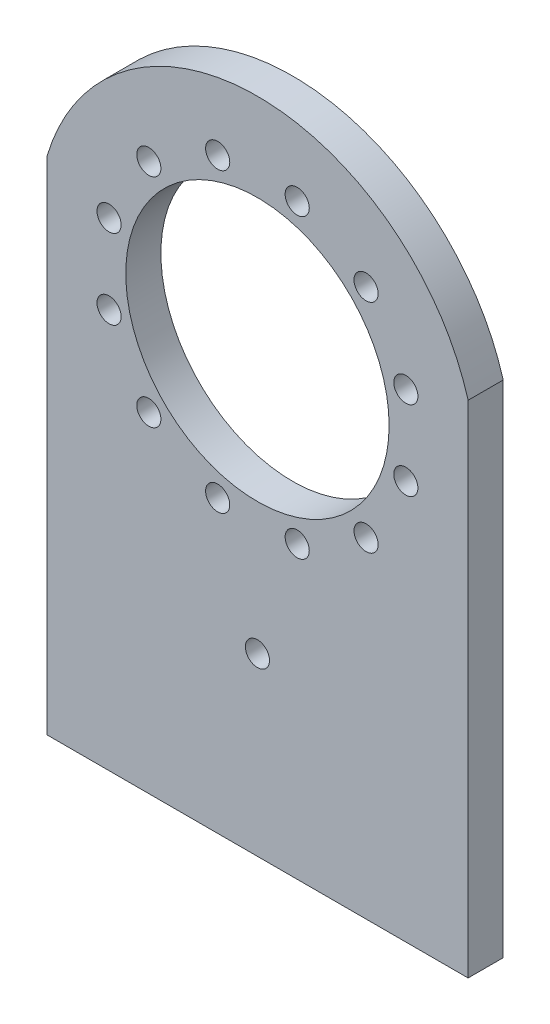
SolidWorks part; units mm, degrees
ref_plane "前视基准面" through (0, 0, 0) normal (0, 0, 1) x (1, 0, 0)
ref_plane "上视基准面" through (0, 0, 0) normal (0, 1, 0) x (1, 0, 0)
ref_plane "右视基准面" through (0, 0, 0) normal (1, 0, 0) x (0, 0, -1)
other "Configuration Table"
sketch "草图1" plane through (0, 0, 0) normal (0, 0, 1) x (1, 0, 0)
  line L0 (0, 0) -> (0, 150.9585) construction
  line L3 (-48, 114) -> (-48, 0)
  line L4 (-48, 0) -> (48, 0)
  line L5 (48, 114) -> (48, 0)
  circle A0 centre (0, 100) radius 30
  arc A2 (48, 114) -> (-48, 114) centre (0, 100) ccw
  dimension "D3" = 60
  dimension "D4" = 50
  dimension "D1" = 96
  dimension "D2" = 100
extrude "凸台-拉伸1" add sketch "草图1" along normal blind 8
sketch "草图2" plane through (0, 0, 0) normal (0, -1, 0) x (1, 0, 0)
  line L0 (-53.8408, 4) -> (58.1589, 4) construction
  line L1 (0, 20.308) -> (0, -17.9139) construction
  line L2 (-48, 8) -> (48, 8) construction
  line L3 (-48, 0) -> (48, 0) construction
  circle A0 centre (35, 4) radius 2.75
  circle A1 centre (-35, 4) radius 2.75
  dimension "D2" = 5.5
  dimension "D1" = 70
extrude "切除-拉伸1" cut sketch "草图2" against normal blind 50
sketch "草图3" plane through (0, 0, 8) normal (0, 0, 1) x (1, 0, 0)
  line L0 (0, 0) -> (0, 95.092) construction
  circle A0 centre (0, 40) radius 2.75
  dimension "D1" = 5.5
  dimension "D2" = 40
extrude "切除-拉伸2" cut sketch "草图3" against normal blind 20
sketch "草图4" plane through (0, 0, 8) normal (0, 0, 1) x (1, 0, 0)
  line L0 (0, 100) -> (0, 148.0466) construction
  line L1 (0, 100) -> (14.5496, 154.2997) construction
  circle A0 centre (9.0587, 133.8074) radius 2.75
  circle A1 centre (24.7487, 124.7487) radius 2.75
  circle A2 centre (33.8074, 109.0587) radius 2.75
  circle A3 centre (33.8074, 90.9413) radius 2.75
  circle A4 centre (24.7487, 75.2513) radius 2.75
  circle A5 centre (9.0587, 66.1926) radius 2.75
  circle A6 centre (-9.0587, 66.1926) radius 2.75
  circle A7 centre (-24.7487, 75.2513) radius 2.75
  circle A8 centre (-33.8074, 90.9413) radius 2.75
  circle A9 centre (-33.8074, 109.0587) radius 2.75
  circle A10 centre (-24.7487, 124.7487) radius 2.75
  circle A11 centre (-9.0587, 133.8074) radius 2.75
  point P31 (0, 100)
  dimension "D1" = 5.5
  dimension "D2" = 35
  dimension "D3" = 15
  dimension "D4" = 12
extrude "切除-拉伸3" cut sketch "草图4" against normal blind 10
